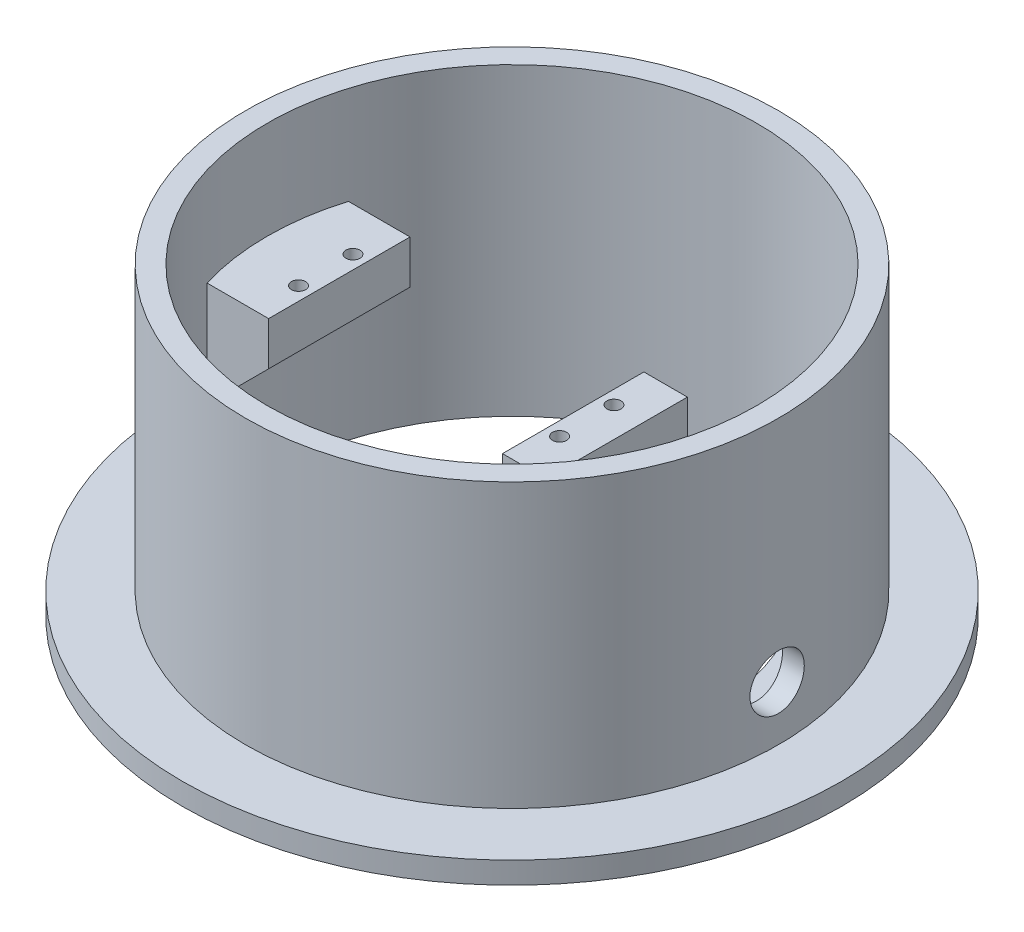
SolidWorks part; units mm, degrees
ref_plane "Front Plane" through (0, 0, 0) normal (0, 0, 1) x (1, 0, 0)
ref_plane "Top Plane" through (0, 0, 0) normal (0, 1, 0) x (1, 0, 0)
ref_plane "Right Plane" through (0, 0, 0) normal (1, 0, 0) x (0, 0, -1)
sketch "Sketch1" plane through (0, 0, 0) normal (0, 1, 0) x (1, 0, 0)
  circle A0 centre (0, 0) radius 60.625
  circle A1 centre (0, 0) radius 45
  dimension "D1" = 121.25
  dimension "D2" = 90
extrude "Boss-Extrude1" add sketch "Sketch1" along normal blind 4 contours A0
sketch "Sketch2" plane through (0, 4, 0) normal (0, 1, 0) x (1, 0, 0)
  circle A0 centre (0, 0) radius 45 construction
  circle A1 centre (0, 0) radius 45
  circle A2 centre (0, 0) radius 49
  dimension "D1" = 4
extrude "Boss-Extrude2" add sketch "Sketch2" along normal blind 52
ref_plane "Plane1" through (0, 36, 0) normal (0, 1, 0) x (1, 0, 0)
sketch "Sketch4" plane through (0, 0, 0) normal (0, 0, 1) x (1, 0, 0)
  line L0 (-60.625, 0) -> (60.625, 0) construction
  line L1 (11.25, 38) -> (19.25, 38)
  line L2 (11.25, 38) -> (11.25, 0)
  line L3 (11.25, 0) -> (19.25, 0)
  line L4 (19.25, 38) -> (19.25, 0)
  line L5 (49, 56) -> (-49, 56) construction
  line L6 (-45, 56) -> (-45, 4)
  line L7 (-31.75, 38) -> (-46.75, 38)
  line L8 (-31.75, 38) -> (-31.75, 30)
  line L9 (-31.75, 30) -> (-46.75, 30)
  line L10 (-46.75, 38) -> (-46.75, 30)
  line L11 (60.625, 4) -> (-60.625, 4) construction
  line L12 (-31.75, 30) -> (-45, 16.75)
  dimension "D1" = 11.25
  dimension "D2" = 8
  dimension "D3" = 18
  dimension "D4" = 43
  dimension "D5" = 15
  dimension "D6" = 8
  dimension "D7" = 45
  dimension "D8" = 18
extrude "Boss-Extrude4" add sketch "Sketch4" along normal mid plane 26 contours L9 L8 L7 L6 | L12 L9 L6 | L1 L4 L3 L2
sketch "Sketch5" plane through (0, 0, 0) normal (0, -1, 0) x (1, 0, 0)
  line L0 (11.25, 13) -> (29.0674, 34.3524)
  line L1 (11.25, -13) -> (29.0674, -34.3524)
  line L2 (11.25, 13) -> (11.25, -13)
  circle A0 centre (0, 0) radius 45 construction
  arc A1 (29.0674, -34.3524) -> (29.0674, 34.3524) centre (0, 0) ccw
extrude "Boss-Extrude5" add sketch "Sketch5" against normal up to surface (4 mm away) contours L0 A1 L1 L2 up to face at (0, 4, 60.625)
sketch "Sketch7" plane through (0, 38, 0) normal (0, 1, 0) x (1, 0, 0)
  line L0 (-31.75, -13) -> (-31.75, 13) construction
  circle A0 centre (-34.25, 5) radius 1.3
  circle A1 centre (-34.25, -5) radius 1.3
  circle A2 centre (13.75, 5) radius 1.3
  circle A3 centre (13.75, -5) radius 1.3
  dimension "D1" = 2.6
  dimension "D2" = 2.6
  dimension "D3" = 10
  dimension "D4" = 5
  dimension "D5" = 2.5
  dimension "D7" = 48
  dimension "D6" = 2
extrude "Cut-Extrude4" cut sketch "Sketch7" against normal blind 7.2
sketch "Sketch9" plane through (11.25, 0, 0) normal (-1, 0, 0) x (0, 0, 1)
  line L0 (13, 0) -> (-13, 0) construction
  line L1 (-5, 29) -> (5, 29)
  line L2 (-5, 29) -> (-5, 0)
  line L3 (-5, 0) -> (5, 0)
  line L4 (5, 29) -> (5, 0)
  line L5 (-5, 29) -> (5, 0) construction
  line L6 (-5, 0) -> (5, 29) construction
  line L7 (0, 0) -> (0, 29) construction
  line L8 (13, 38) -> (-13, 38) construction
  line L10 (5, 5) -> (-5, 5)
  point P0 (0, 14.5)
  dimension "D1" = 10
  dimension "D2" = 9
  dimension "D3" = 5
extrude "Cut-Extrude7" cut sketch "Sketch9" against normal up to surface (8 mm away) contours L10 L4 L1 L2 up to face at (19.25, 21, 0)
ref_plane "Plane2" through (49, 0, 0) normal (1, 0, 0) x (0, 0, -1)
sketch "Sketch11" plane through (49, 0, 0) normal (1, 0, 0) x (0, 0, -1)
  circle A0 centre (0, 14) radius 5
  dimension "D1" = 10
  dimension "D2" = 14
extrude "Cut-Extrude8" cut sketch "Sketch11" against normal up to next
sketch "Sketch12" plane through (0, 4, 0) normal (0, 1, 0) x (1, 0, 0)
  line L5 (27.25, 19.6878) -> (27.25, -19.6878)
  line L6 (27.25, 19.6878) -> (27.25, -19.6878)
  line L9 (24.25, 16.0926) -> (24.25, -16.0926)
  line L10 (19.25, -13) -> (19.25, 13) construction
  line L18 (27.25, -19.6878) -> (29.4795, -22.3597)
  line L19 (29.4795, 22.3597) -> (27.25, 19.6878)
  line L21 (24.25, -16.0926) -> (29.4795, -22.3597)
  line L22 (29.4795, 22.3597) -> (24.25, 16.0926)
  arc A2 (29.4795, -22.3597) -> (29.4795, 22.3597) centre (0, 0) ccw
  arc A3 (29.4795, -22.3597) -> (29.4795, 22.3597) centre (0, 0) ccw
  dimension "D2" = 5
  dimension "D1" = 8
extrude "Cut-Extrude9" cut sketch "Sketch12" against normal through all contours L21 A3 L22 L6 | L6 L22 L9 L21
sketch "Sketch14" plane through (0, 4, 0) normal (0, 1, 0) x (1, 0, 0)
  line L0 (0, 0) -> (-38.8909, 38.8909) construction
  line L1 (11.25, 13) -> (19.25, 13) construction
  circle A0 centre (-38.8909, 38.8909) radius 1.5
  circle A1 centre (38.8909, 38.8909) radius 1.5
  circle A2 centre (38.8909, -38.8909) radius 1.5
  circle A3 centre (-38.8909, -38.8909) radius 1.5
  point P15 (0, 0)
  dimension "D1" = 3
  dimension "D2" = 55
  dimension "D3" = 135
  dimension "D4" = 4
